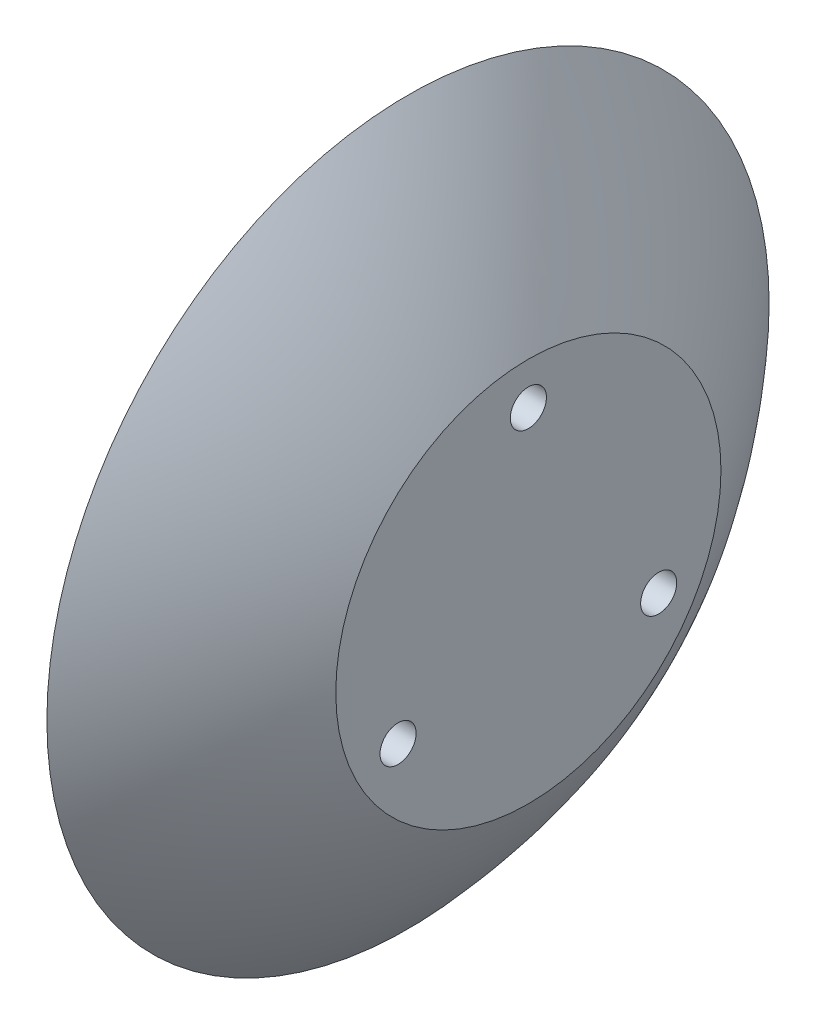
SolidWorks part; units mm, degrees
ref_plane "Alzado" through (0, 0, 0) normal (0, 0, 1) x (1, 0, 0)
ref_plane "Planta" through (0, 0, 0) normal (0, 1, 0) x (1, 0, 0)
ref_plane "Vista lateral" through (0, 0, 0) normal (1, 0, 0) x (0, 0, -1)
sketch "Croquis1" plane through (0, 0, 0) normal (0, 0, 1) x (1, 0, 0)
  line L0 (0, 0) -> (0, 30)
  line L1 (0, 0) -> (10, 0)
  line L2 (22.475, 0) -> (-58.2243, 0) construction
  line L3 (10, 0) -> (10, 16)
  arc A0 (10, 16) -> (0, 30) centre (-56.6101, -21.0072) ccw
  dimension "D1" = 152.4
  dimension "D2" = 10
  dimension "D3" = 30
  dimension "D4" = 16
revolve "Revolución1" add sketch "Croquis1" angle 360 about L2
sketch "Croquis3" plane through (10, 0, 0) normal (1, 0, 0) x (0, 0, -1)
  line L0 (0, 0) -> (0, 12.5) construction
  line L1 (0, 0) -> (0, 12.5) construction
  line L2 (0, 0) -> (10.8253, -6.25) construction
  circle A0 centre (0, 12.5) radius 1.5
  circle A1 centre (0, 0) radius 12.5 construction
  circle A2 centre (10.8253, -6.25) radius 1.5
  circle A3 centre (-10.8253, -6.25) radius 1.5
  point P5 (0, 0)
  dimension "D1" = 3
  dimension "D2" = 25
  dimension "D3" = 3
  dimension "D4" = 120
  dimension "D5" = 12.5
extrude "Cortar-Extruir1" cut sketch "Croquis3" against normal blind 10
